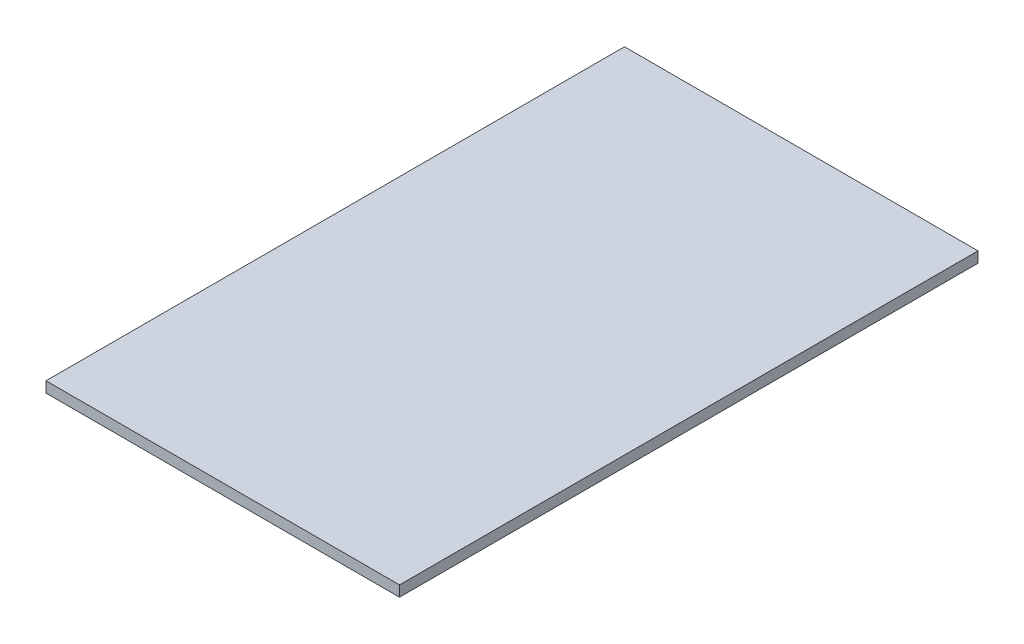
SolidWorks part; units mm, degrees
ref_plane "Front Plane" through (0, 0, 0) normal (0, 0, 1) x (1, 0, 0)
ref_plane "Top Plane" through (0, 0, 0) normal (0, 1, 0) x (1, 0, 0)
ref_plane "Right Plane" through (0, 0, 0) normal (1, 0, 0) x (0, 0, -1)
sketch "Sketch1" plane through (0, 0, 0) normal (0, 1, 0) x (1, 0, 0)
  line L1 (-82.5, -135) -> (82.5, -135)
  line L2 (-82.5, -135) -> (-82.5, 135)
  line L3 (-82.5, 135) -> (82.5, 135)
  line L4 (82.5, -135) -> (82.5, 135)
  line L5 (-82.5, -135) -> (82.5, 135) construction
  line L6 (-82.5, 135) -> (82.5, -135) construction
  point P0 (0, 0)
  dimension "D1" = 165
  dimension "D2" = 270
extrude "Boss-Extrude1" add sketch "Sketch1" along normal blind 5
